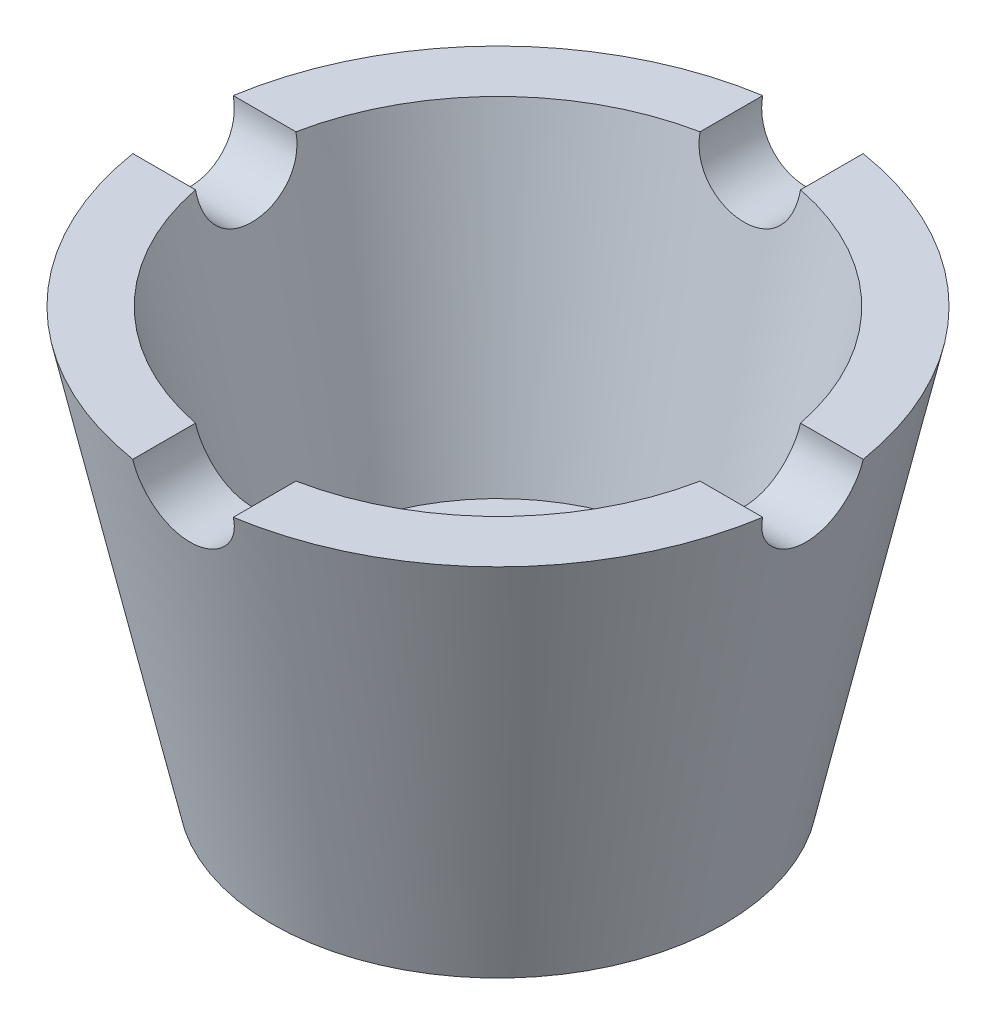
SolidWorks part; units mm, degrees
material "AISI 1020"
ref_plane "Front Plane" through (0, 0, 0) normal (0, 0, 1) x (1, 0, 0)
ref_plane "Top Plane" through (0, 0, 0) normal (0, 1, 0) x (1, 0, 0)
ref_plane "Right Plane" through (0, 0, 0) normal (1, 0, 0) x (0, 0, -1)
sketch "Sketch1" plane through (0, 0, 0) normal (0, 0, 1) x (1, 0, 0)
  line L0 (11, 0) -> (22.5, 0)
  line L1 (22.5, 0) -> (31.7537, 42)
  line L2 (31.7537, 42) -> (25.6098, 42)
  line L3 (25.6098, 42) -> (19, 12)
  line L4 (19, 12) -> (11, 12)
  line L5 (11, 12) -> (11, 0)
  line L6 (0, 0) -> (0, 42) construction
  dimension "D1" = 12
  dimension "D2" = 22.5
  dimension "D3" = 42
  dimension "D4" = 19
  dimension "D5" = 11
  dimension "D6" = 6
revolve "Revolve1" add sketch "Sketch1" angle 360 about L6
sketch "Sketch2" plane through (0, 0, 0) normal (0, 0, 1) x (1, 0, 0)
  line L0 (31.7537, 42) -> (-31.7537, 42) construction
  circle A0 centre (0, 42) radius 5
  dimension "D1" = 10
extrude "Cut-Extrude1" cut sketch "Sketch2" against normal mid plane 80
pattern_circular "CirPattern1" count 4 over 360 about axis through (0, 0, 0) along (0, 1, 0) of "Cut-Extrude1"
